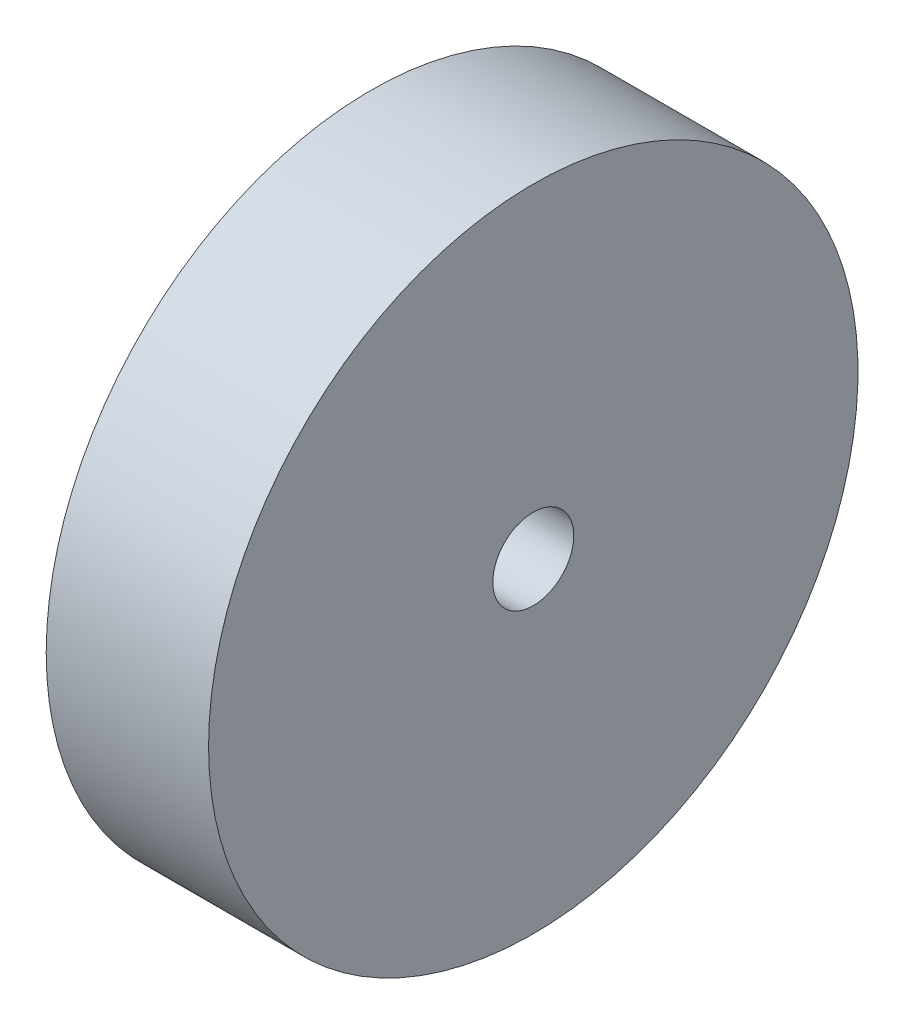
SolidWorks part; units mm, degrees
material "AISI 304"
ref_plane "Front Plane" through (0, 0, 0) normal (0, 0, 1) x (1, 0, 0)
ref_plane "Top Plane" through (0, 0, 0) normal (0, 1, 0) x (1, 0, 0)
ref_plane "Right Plane" through (0, 0, 0) normal (1, 0, 0) x (0, 0, -1)
sketch "Sketch1" plane through (0, 0, 0) normal (1, 0, 0) x (0, 0, -1)
  circle A0 centre (0, 0) radius 152.4
  dimension "D1" = 304.8
extrude "Boss-Extrude1" add sketch "Sketch1" along normal blind 76.2
sketch "Sketch2" plane through (76.2, 0, 0) normal (1, 0, 0) x (0, 0, -1)
  circle A0 centre (0, 0) radius 19
  dimension "D1" = 37.9999
extrude "Cut-Extrude1" cut sketch "Sketch2" against normal through all
